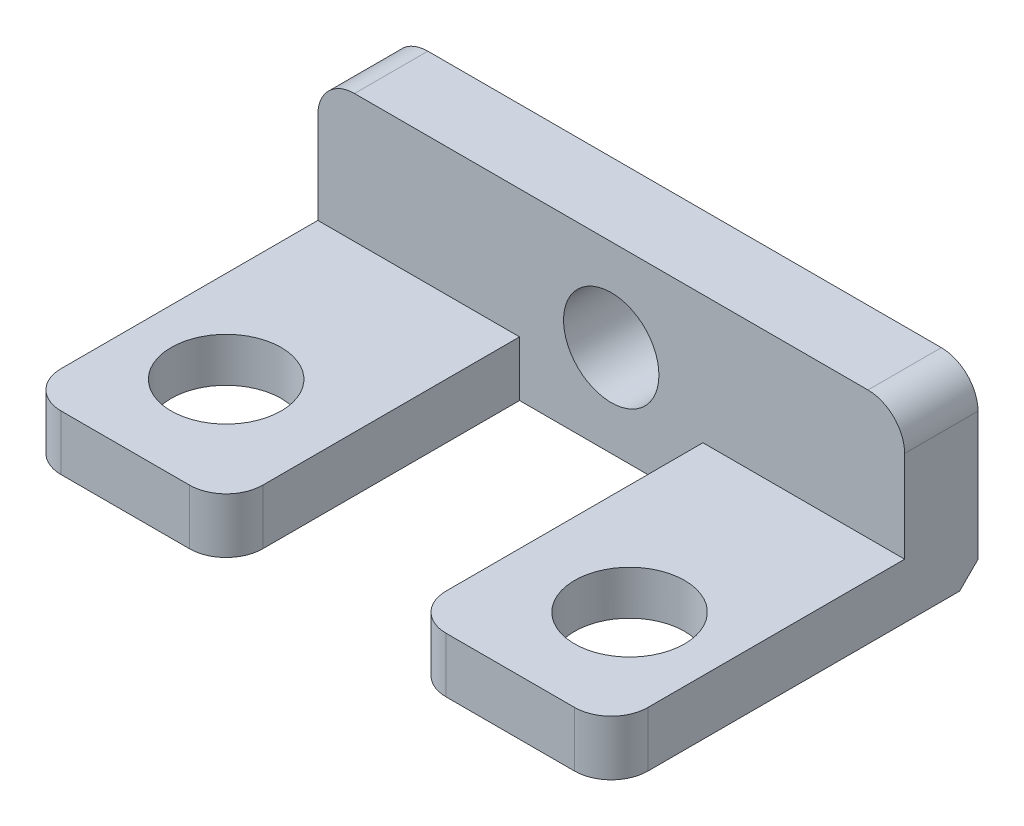
SolidWorks part; units mm, degrees
material "6061 合金"
ref_plane "前视基准面" through (0, 0, 0) normal (0, 0, 1) x (1, 0, 0)
ref_plane "上视基准面" through (0, 0, 0) normal (0, 1, 0) x (1, 0, 0)
ref_plane "右视基准面" through (0, 0, 0) normal (1, 0, 0) x (0, 0, -1)
sketch "草图1" plane through (0, 0, 0) normal (0, 0, 1) x (1, 0, 0)
  line L1 (0, 0) -> (16, 0)
  line L2 (0, 0) -> (0, 5)
  line L3 (0, 5) -> (16, 5)
  line L4 (16, 0) -> (16, 5)
  dimension "D1" = 5
  dimension "D2" = 16
extrude "凸台-拉伸1" add sketch "草图1" along normal blind 10
sketch "草图2" plane through (0, 0, 10) normal (0, 0, 1) x (1, 0, 0)
  line L0 (16, 0) -> (16, 5) construction
  line L1 (0, 5) -> (16, 5)
  line L2 (0, 5) -> (0, 1.5038)
  line L3 (0, 1.5038) -> (16, 1.5038)
  line L4 (16, 5) -> (16, 1.5038)
  line L5 (0, 0) -> (16, 0) construction
  dimension "D1" = 1.5038
extrude "切除-拉伸1" cut sketch "草图2" against normal offset from surface (8 mm away) 2 up to face at (8, 2.5, 0)
sketch "草图4" plane through (0, 0, 10) normal (0, 0, 1) x (1, 0, 0)
  line L0 (0, 1.5038) -> (16, 1.5038) construction
  line L1 (5.5, 1.5038) -> (10.5, 1.5038)
  line L2 (5.5, 1.5038) -> (5.5, 0)
  line L3 (5.5, 0) -> (10.5, 0)
  line L4 (10.5, 1.5038) -> (10.5, 0)
  line L5 (0, 0) -> (16, 0) construction
  line L6 (0, 1.5038) -> (0, 0) construction
  line L7 (16, 0) -> (16, 1.5038) construction
  point P10 (16, 0.7519)
  dimension "D1" = 5.5
  dimension "D2" = 5.5
extrude "切除-拉伸3" cut sketch "草图4" against normal up to surface (8 mm away) up to face at (8, 3.2519, 2)
sketch "草图3" plane through (0, 0, 2) normal (0, 0, 1) x (1, 0, 0)
  line L0 (8, 5) -> (8, -1.8876) construction
  line L1 (16, 5) -> (0, 5) construction
  line L3 (5.5, 0) -> (10.5, 0) construction
  circle A0 centre (8, 2.5) radius 1.3
  dimension "D1" = 2.6
  dimension "D2" = 2.5
extrude "切除-拉伸2" cut sketch "草图3" against normal blind 2
sketch "草图5" plane through (0, 0, 0) normal (0, -1, 0) x (1, 0, 0)
  line L0 (8, 0) -> (8, 14.4956) construction
  line L1 (0, 0) -> (16, 0) construction
  line L2 (0, 10) -> (5.5, 10) construction
  circle A0 centre (2.5, 7) radius 1.5
  circle A1 centre (13.5, 7) radius 1.5
  dimension "D1" = 11
  dimension "D2" = 3
  dimension "D3" = 3
extrude "切除-拉伸5" cut sketch "草图5" against normal blind 2
sketch "草图6" plane through (0, 0, 0) normal (0, -1, 0) x (1, 0, 0)
  circle A0 centre (2.5, 7) radius 2
  circle A1 centre (13.5, 7) radius 2
  dimension "D1" = 4
  dimension "D2" = 4
extrude "切除-拉伸6" cut sketch "草图6" against normal blind 0.3
fillet "圆角1" radius 1 2 edges at (0, 5, 1) (16, 5, 1)
fillet "圆角2" radius 1 4 edges at (16, 0.7519, 10) (10.5, 0.7519, 10) (5.5, 0.7519, 10) (0, 0.7519, 10)
chamfer "倒角1" distance 0.5 angle 45 1 edges at (8, 0, 0)
